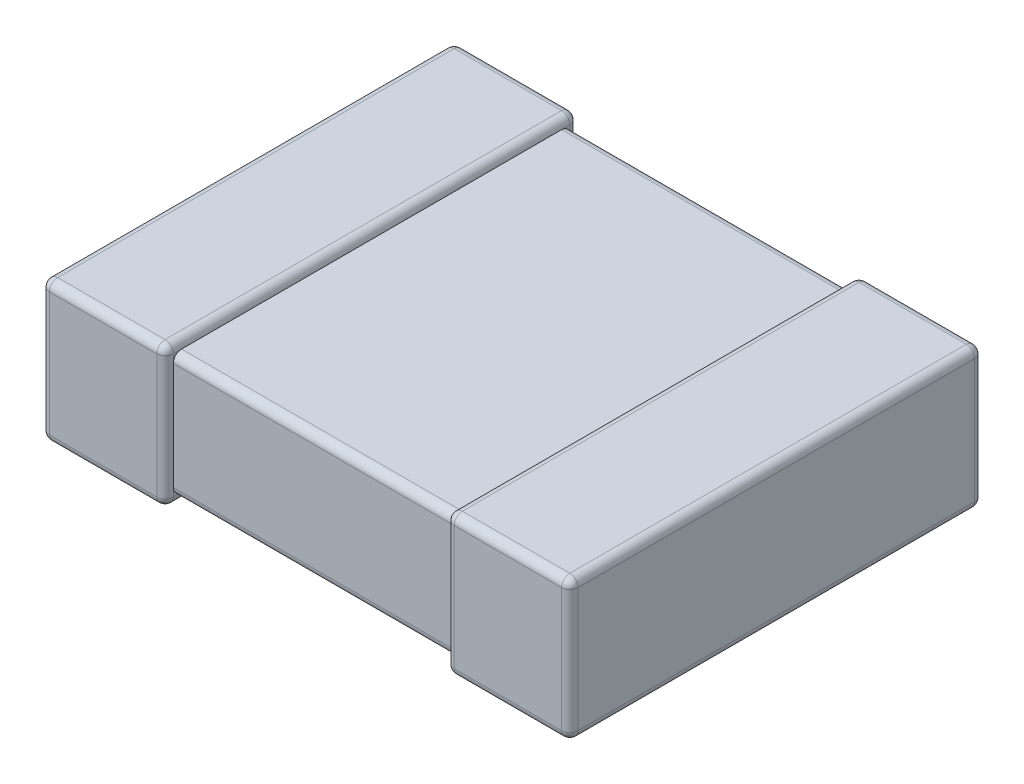
SolidWorks part; units mm, degrees
ref_plane "Front Plane" through (0, 0, 0) normal (0, 0, 1) x (1, 0, 0)
ref_plane "Top Plane" through (0, 0, 0) normal (0, 1, 0) x (1, 0, 0)
ref_plane "Right Plane" through (0, 0, 0) normal (1, 0, 0) x (0, 0, -1)
other "Configuration Table"
ref_plane "Plane4" through (0, 0.05, 0) normal (0, 1, 0) x (1, 0, 0)
sketch "Sketch1" plane through (0, 0.05, 0) normal (0, 1, 0) x (1, 0, 0)
  line L1 (-1.55, 1.2) -> (1.55, 1.2)
  line L2 (-1.55, 1.2) -> (-1.55, -1.2)
  line L3 (-1.55, -1.2) -> (1.55, -1.2)
  line L4 (1.55, 1.2) -> (1.55, -1.2)
  dimension "D1" = 3.1
  dimension "D2" = 1.55
  dimension "D3" = 2.4
  dimension "D4" = 1.2
extrude "Boss-Extrude1" add sketch "Sketch1" along normal blind 0.75
sketch "Sketch2" plane through (0, 0, 0) normal (0, 1, 0) x (1, 0, 0)
  line L0 (-1.55, 1.2) -> (-1.55, -1.2) construction
  line L1 (-1.6, 1.25) -> (-0.85, 1.25)
  line L2 (-1.6, 1.25) -> (-1.6, -1.25)
  line L3 (-1.6, -1.25) -> (-0.85, -1.25)
  line L4 (-0.85, 1.25) -> (-0.85, -1.25)
  line L5 (0.85, 1.25) -> (1.6, 1.25)
  line L6 (0.85, 1.25) -> (0.85, -1.25)
  line L7 (0.85, -1.25) -> (1.6, -1.25)
  line L8 (1.6, 1.25) -> (1.6, -1.25)
  line L9 (1.55, -1.2) -> (1.55, 1.2) construction
  line L10 (-1.55, -1.2) -> (1.55, -1.2) construction
  line L11 (1.55, 1.2) -> (-1.55, 1.2) construction
  dimension "D1" = 0.05
  dimension "D2" = 0.05
  dimension "D3" = 0.75
  dimension "D4" = 0.75
  dimension "D5" = 0.05
  dimension "D6" = 0.05
extrude "Boss-Extrude2" add sketch "Sketch2" along normal offset from surface (0.85 mm away) 0.05 separate body up to face at (0, 0.8, 0) offset beyond the face yes
fillet "Fillet1" radius 0.05 12 edges at (0.85, 0, 0) (1.225, 0, 1.25) (0.85, 0.425, 1.25) (1.6, 0, 0) (1.6, 0.425, 1.25) (0.85, 0.425, -1.25) (1.225, 0, -1.25) (1.6, 0.425, -1.25) (1.6, 0.85, 0) (1.225, 0.85, 1.25) (0.85, 0.85, 0) (1.225, 0.85, -1.25)
fillet "Fillet2" radius 0.05 12 edges at (-0.85, 0.425, -1.25) (-0.85, 0, 0) (-1.225, 0, -1.25) (-1.6, 0, 0) (-1.6, 0.425, -1.25) (-0.85, 0.425, 1.25) (-1.225, 0, 1.25) (-1.6, 0.425, 1.25) (-0.85, 0.85, 0) (-1.225, 0.85, 1.25) (-1.6, 0.85, 0) (-1.225, 0.85, -1.25)
fillet "Fillet3" radius 0.05 12 edges at (1.55, 0.05, 0) (-1.55, 0.05, 0) (1.55, 0.425, -1.2) (-1.55, 0.425, -1.2) (0, 0.05, -1.2) (-1.55, 0.425, 1.2) (1.55, 0.425, 1.2) (0, 0.05, 1.2) (0, 0.8, -1.2) (1.55, 0.8, 0) (0, 0.8, 1.2) (-1.55, 0.8, 0)
equation "\"D2@Sketch1\"=\"D1@Sketch1\"/2"
equation "\"D4@Sketch1\"=\"D3@Sketch1\"/2"
equation "\"D6@Sketch2\"=\"D5@Sketch2\""
equation "\"D4@Sketch2\"=\"D3@Sketch2\""
